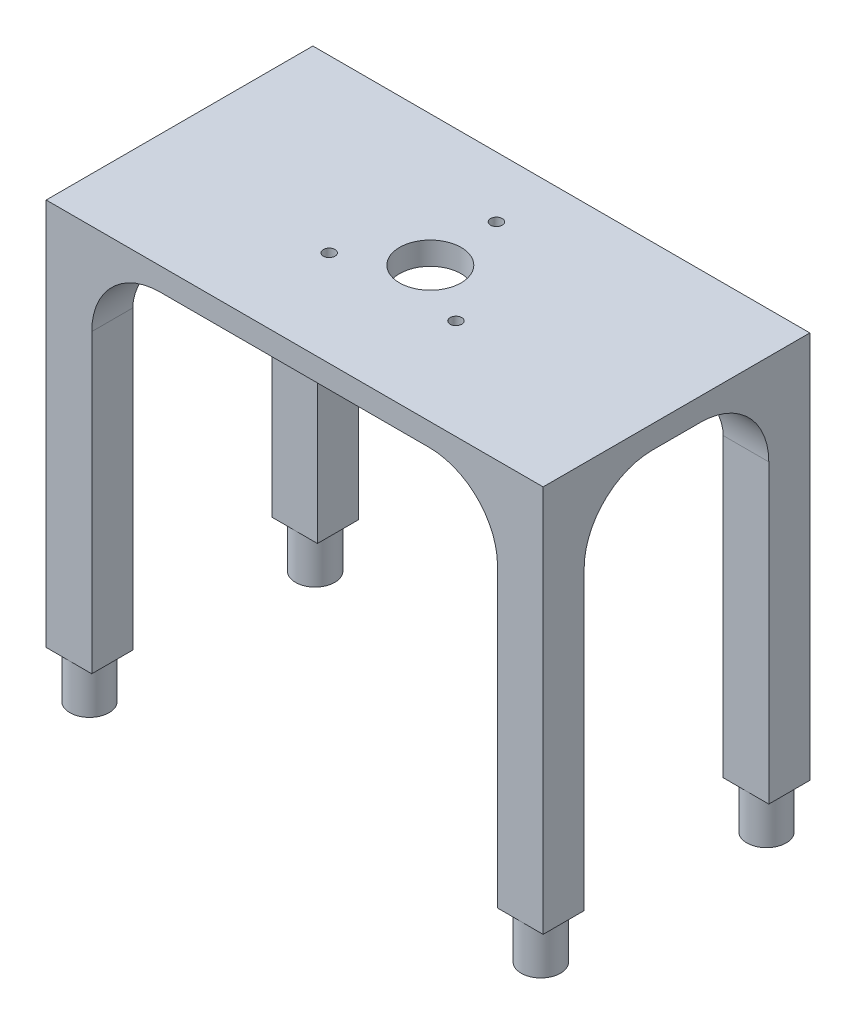
SolidWorks part; units mm, degrees
ref_plane "Front Plane" through (0, 0, 0) normal (0, 0, 1) x (1, 0, 0)
ref_plane "Top Plane" through (0, 0, 0) normal (0, 1, 0) x (1, 0, 0)
ref_plane "Right Plane" through (0, 0, 0) normal (1, 0, 0) x (0, 0, -1)
sketch "Sketch1" plane through (0, 0, 0) normal (0, 1, 0) x (1, 0, 0)
  line L0 (0, 0) -> (72.9856, 0) construction
  line L1 (72.9856, 0) -> (-101.1225, 0) construction
  line L2 (0, -25.5652) -> (0, 27.1045) construction
  line L3 (49.5, 0) -> (49.5, 52.2141) construction
  circle A0 centre (49.5, 0) radius 4.3
  circle A1 centre (-49.5, 0) radius 4.3
  circle A2 centre (49.5, 49.5) radius 4.3
  circle A3 centre (-49.5, 49.5) radius 4.3
  dimension "D2" = 8.6
  dimension "D4" = 8.6
  dimension "D1" = 49.5
  dimension "D3" = 49.5
extrude "Boss-Extrude1" add sketch "Sketch1" along normal blind 10
sketch "Sketch2" plane through (0, 10, 0) normal (0, 1, 0) x (1, 0, 0)
  line L0 (0, 0) -> (0, 54.4329) construction
  line L1 (44.5, -4.5) -> (54.5, -4.5)
  line L2 (44.5, -4.5) -> (44.5, 4.5)
  line L3 (44.5, 4.5) -> (54.5, 4.5)
  line L4 (54.5, -4.5) -> (54.5, 4.5)
  line L5 (44.5, -4.5) -> (54.5, 4.5) construction
  line L6 (44.5, 4.5) -> (54.5, -4.5) construction
  line L9 (-44.5, 4.5) -> (-54.5, 4.5)
  line L10 (-54.5, -4.5) -> (-54.5, 4.5)
  line L11 (-44.5, -4.5) -> (-54.5, -4.5)
  line L12 (-44.5, -4.5) -> (-44.5, 4.5)
  line L13 (54.5, 54) -> (44.5, 54)
  line L14 (-54.5, 45) -> (-44.5, 45)
  line L15 (-54.5, 45) -> (-54.5, 54)
  line L16 (-54.5, 54) -> (-44.5, 54)
  line L17 (-44.5, 45) -> (-44.5, 54)
  line L18 (-54.5, 45) -> (-44.5, 54) construction
  line L19 (-54.5, 54) -> (-44.5, 45) construction
  line L20 (44.5, 45) -> (44.5, 54)
  line L21 (54.5, 45) -> (44.5, 45)
  line L22 (54.5, 45) -> (54.5, 54)
  point P0 (49.5, 0)
  point P16 (-49.5, 49.5)
  dimension "D1" = 9
  dimension "D2" = 10
  dimension "D3" = 9
  dimension "D4" = 10
extrude "Boss-Extrude2" add sketch "Sketch2" along normal blind 80
sketch "Sketch3" plane through (0, 90, 0) normal (0, 1, 0) x (1, 0, 0)
  line L1 (-54.5, -4.5) -> (54.5, -4.5)
  line L2 (-54.5, -4.5) -> (-54.5, 54)
  line L3 (-54.5, 54) -> (54.5, 54)
  line L4 (54.5, -4.5) -> (54.5, 54)
extrude "Boss-Extrude3" add sketch "Sketch3" along normal blind 5
fillet "Fillet1" radius 15 8 edges at (-44.5, 90, -49.5) (-49.5, 90, -45) (-44.5, 90, 0) (-49.5, 90, -4.5) (44.5, 90, -49.5) (49.5, 90, -45) (49.5, 90, -4.5) (44.5, 90, 0)
sketch "Sketch4" plane through (0, 95, 0) normal (0, 1, 0) x (1, 0, 0)
  line L0 (54.5, 54) -> (-54.5, 54) construction
  line L3 (-54.5, -4.5) -> (54.5, -4.5) construction
  line L5 (54.5, -4.5) -> (54.5, 54) construction
  line L6 (-54.5, 54) -> (-54.5, -4.5) construction
  circle A0 centre (-0.9651, 40.722) radius 1.275
  circle A1 centre (13.4089, 17.472) radius 1.275
  circle A2 centre (-13.4204, 16.5022) radius 1.275
  circle A3 centre (0.003, 25.2522) radius 6.75
  point P0 (0, 0)
  point P22 (2.1685, 53.5)
  dimension "D1" = 2.55
  dimension "D2" = 2.55
  dimension "D3" = 13.5
  dimension "D4" = 2.55
  dimension "D9" = 21.0022
  dimension "D5" = 15.5
  dimension "D6" = 15.5
  dimension "D7" = 28.7478
  dimension "D8" = 54.497
  dimension "D10" = 41.0796
  dimension "D11" = 26.8468
  dimension "D12" = 23.25
extrude "Cut-Extrude1" cut sketch "Sketch4" against normal blind 5
